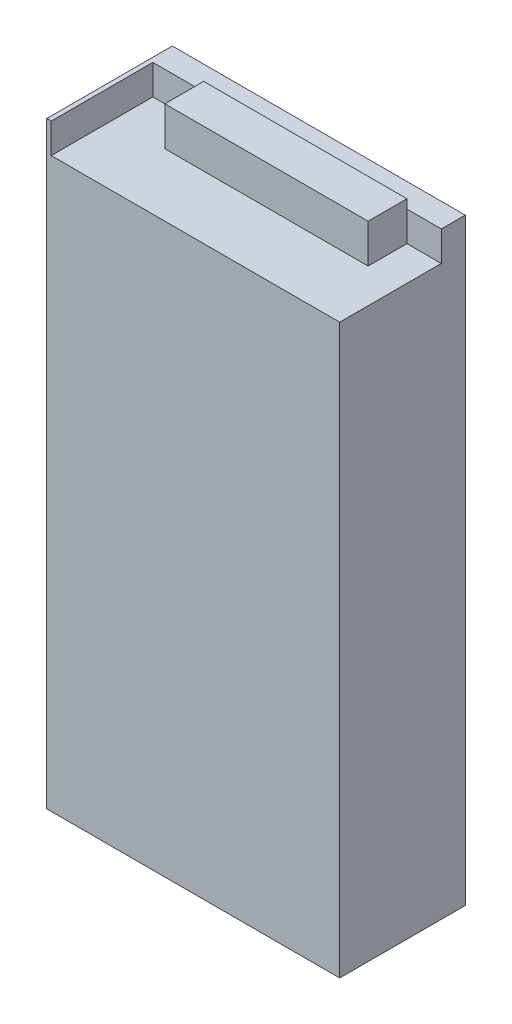
SolidWorks part; units mm, degrees
ref_plane "Спереди" through (0, 0, 0) normal (0, 0, 1) x (1, 0, 0)
ref_plane "Сверху" through (0, 0, 0) normal (0, 1, 0) x (1, 0, 0)
ref_plane "Справа" through (0, 0, 0) normal (1, 0, 0) x (0, 0, -1)
sketch "Эскиз1" plane through (0, 0, 0) normal (0, 0, 1) x (1, 0, 0)
  line L1 (-18.1906, 32.397) -> (79.8094, 32.397)
  line L2 (-18.1906, 32.397) -> (-18.1906, -167.603)
  line L3 (-18.1906, -167.603) -> (79.8094, -167.603)
  line L4 (79.8094, 32.397) -> (79.8094, -167.603)
  dimension "D1" = 98
  dimension "D2" = 200
extrude "Бобышка-Вытянуть1" add sketch "Эскиз1" along normal blind 42
sketch "Эскиз2" plane through (0, 0, 0) normal (0, 0, 1) x (1, 0, 0)
  line L0 (30.8094, -167.603) -> (30.8094, 32.397) construction
  line L1 (-18.1906, -167.603) -> (79.8094, -167.603) construction
  line L2 (79.8094, 32.397) -> (-18.1906, 32.397) construction
  line L3 (-26.2596, -30.103) -> (84.4299, -30.103) construction
  line L4 (-18.1906, -150.103) -> (79.8094, -150.103) construction
  line L5 (-18.1906, 32.397) -> (-18.1906, -167.603) construction
  line L6 (79.8094, -167.603) -> (79.8094, 32.397) construction
  line L7 (-9.1906, -30.103) -> (-9.1906, -150.103) construction
  line L8 (70.8094, -30.103) -> (70.8094, -150.103) construction
  circle A0 centre (-9.1906, -30.103) radius 1.5
  circle A1 centre (70.8094, -30.103) radius 1.5
  circle A2 centre (-9.1906, -150.103) radius 1.5
  circle A3 centre (70.8094, -150.103) radius 1.5
  dimension "D1" = 40
  dimension "D3" = 3
  dimension "D4" = 3
  dimension "D5" = 3
  dimension "D6" = 3
  dimension "D2" = 40
  dimension "D7" = 17.5
  dimension "D8" = 120
extrude "Вырез-Вытянуть3" cut sketch "Эскиз2" along normal blind 5
sketch "Эскиз3" plane through (0, 0, 42) normal (0, 0, 1) x (1, 0, 0)
  line L0 (79.8094, 32.397) -> (-18.1906, 32.397) construction
  line L1 (-16.6906, 32.397) -> (79.8094, 32.397)
  line L2 (-16.6906, 32.397) -> (-16.6906, 22.397)
  line L3 (-16.6906, 22.397) -> (79.8094, 22.397)
  line L4 (79.8094, 32.397) -> (79.8094, 22.397)
  line L5 (79.8094, -167.603) -> (79.8094, 32.397) construction
  line L6 (-18.1906, 32.397) -> (-18.1906, -167.603) construction
  dimension "D1" = 1.5
  dimension "D2" = 10
extrude "Вырез-Вытянуть4" cut sketch "Эскиз3" against normal blind 34
sketch "Эскиз4" plane through (0, 22.397, 0) normal (0, 1, 0) x (1, 0, 0)
  line L0 (-16.6906, -8) -> (79.8094, -8) construction
  line L1 (0.3094, -8) -> (68.3094, -8)
  line L2 (0.3094, -8) -> (0.3094, -21)
  line L3 (0.3094, -21) -> (68.3094, -21)
  line L4 (68.3094, -8) -> (68.3094, -21)
  line L5 (-16.6906, -8) -> (-16.6906, -42) construction
  dimension "D1" = 68
  dimension "D2" = 17
  dimension "D3" = 13
extrude "Бобышка-Вытянуть2" add sketch "Эскиз4" along normal blind 13
